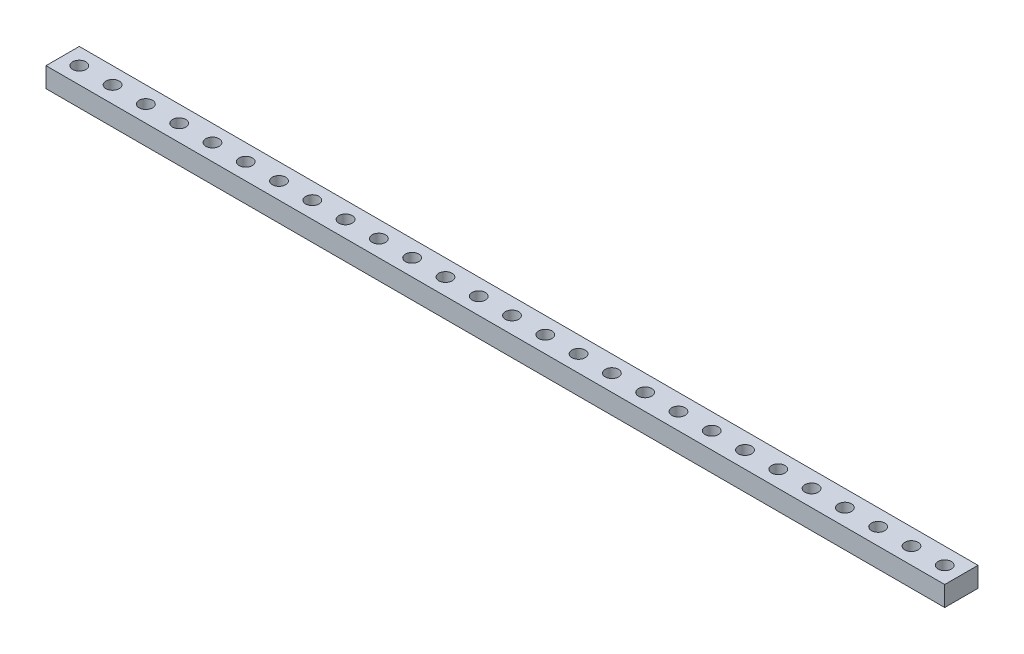
SolidWorks part; units mm, degrees
ref_plane "Plan de face" through (0, 0, 0) normal (0, 0, 1) x (1, 0, 0)
ref_plane "Plan de dessus" through (0, 0, 0) normal (0, 1, 0) x (1, 0, 0)
ref_plane "Plan de droite" through (0, 0, 0) normal (1, 0, 0) x (0, 0, -1)
sketch "Esquisse1" plane through (0, 0, 0) normal (0, 1, 0) x (1, 0, 0)
  line L0 (0, 0) -> (140, 0)
  line L1 (0, 0) -> (-140, 0)
  line L2 (-140, 0) -> (-140, 10)
  line L3 (-140, 10) -> (140, 10)
  line L4 (140, 10) -> (140, 0)
  line L5 (-140, 5) -> (-135, 5) construction
  circle A0 centre (-135, 5) radius 2
  circle A1 centre (-125, 5) radius 2
  circle A2 centre (-115, 5) radius 2
  circle A3 centre (-105, 5) radius 2
  circle A4 centre (-95, 5) radius 2
  circle A5 centre (-85, 5) radius 2
  circle A6 centre (-75, 5) radius 2
  circle A7 centre (-65, 5) radius 2
  circle A8 centre (-55, 5) radius 2
  circle A9 centre (-45, 5) radius 2
  circle A10 centre (-35, 5) radius 2
  circle A11 centre (-25, 5) radius 2
  circle A12 centre (-15, 5) radius 2
  circle A13 centre (-5, 5) radius 2
  circle A14 centre (5, 5) radius 2
  circle A15 centre (15, 5) radius 2
  circle A16 centre (25, 5) radius 2
  circle A17 centre (35, 5) radius 2
  circle A18 centre (45, 5) radius 2
  circle A19 centre (55, 5) radius 2
  circle A20 centre (65, 5) radius 2
  circle A21 centre (75, 5) radius 2
  circle A22 centre (85, 5) radius 2
  circle A23 centre (95, 5) radius 2
  circle A24 centre (105, 5) radius 2
  circle A25 centre (115, 5) radius 2
  circle A26 centre (125, 5) radius 2
  circle A27 centre (135, 5) radius 2
  dimension "D3" = 28
  dimension "D1" = 140
  dimension "D2" = 140
extrude "Boss.-Extru.1" add sketch "Esquisse1" along normal blind 6
sketch "Esquisse2" plane through (0, 6, 0) normal (0, 1, 0) x (1, 0, 0)
  line L0 (-140, 10) -> (130, 10) construction
  line L1 (140, 10) -> (-140, 10) construction
  line L2 (130, 10) -> (130, 0)
  line L3 (-140, 0) -> (140, 0) construction
  line L4 (130, 0) -> (140, 0)
  line L5 (140, 0) -> (140, 10)
  line L6 (140, 10) -> (130, 10)
extrude "Enlèv. mat.-Extru.1" cut sketch "Esquisse2" against normal up to next
